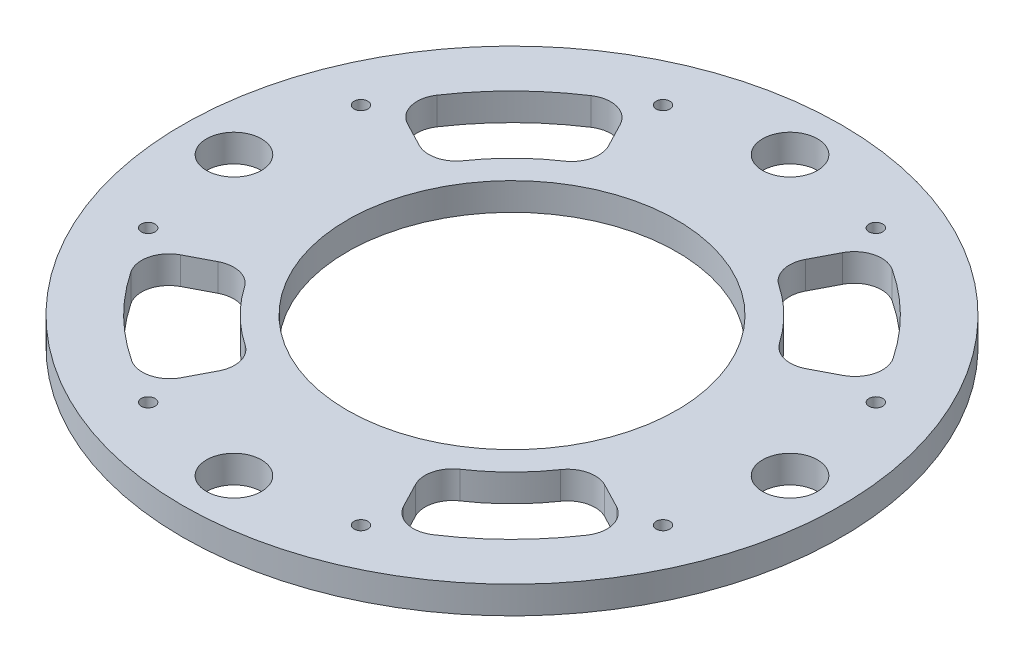
SolidWorks part; units mm, degrees
material "Acrylic (Medium-high impact)"
ref_plane "Front Plane" through (0, 0, 0) normal (0, 0, 1) x (1, 0, 0)
ref_plane "Top Plane" through (0, 0, 0) normal (0, 1, 0) x (1, 0, 0)
ref_plane "Right Plane" through (0, 0, 0) normal (1, 0, 0) x (0, 0, -1)
sketch "Sketch1" plane through (0, 0, 0) normal (0, 1, 0) x (1, 0, 0)
  circle A0 centre (0, 0) radius 76.2
  dimension "D1" = 152.4
extrude "Boss-Extrude1" add sketch "Sketch1" along normal blind 6.35
sketch "Sketch2" plane through (0, 6.35, 0) normal (0, 1, 0) x (1, 0, 0)
  circle A0 centre (0, 0) radius 35
  dimension "D1" = 70
extrude "Cut-Extrude1" cut sketch "Sketch2" against normal blind 6.35
sketch "Sketch3" plane through (0, 6.35, 0) normal (0, 1, 0) x (1, 0, 0)
  line L0 (-76.2, 0) -> (76.2, 0) construction
  line L1 (-51.5875, 51.5875) -> (51.5875, 51.5875) construction
  line L2 (-51.5875, 51.5875) -> (-51.5875, -51.5875) construction
  line L3 (-51.5875, -51.5875) -> (51.5875, -51.5875) construction
  line L4 (51.5875, 51.5875) -> (51.5875, -51.5875) construction
  circle A0 centre (0, 0) radius 76.2 construction
  circle A1 centre (-64.2875, 0) radius 6.35
  circle A2 centre (64.2875, 0) radius 6.35
  dimension "D1" = 12.7
  dimension "D2" = 12.7
  dimension "D3" = 12.7
  dimension "D4" = 12.7
extrude "Cut-Extrude2" cut sketch "Sketch3" against normal blind 10
sketch "Sketch4" plane through (0, 6.35, 0) normal (0, 1, 0) x (1, 0, 0)
  line L1 (50, -50) -> (-50, -50) construction
  line L2 (50, -50) -> (50, 50) construction
  line L3 (50, 50) -> (-50, 50) construction
  line L4 (-50, -50) -> (-50, 50) construction
  line L5 (50, -50) -> (-50, 50) construction
  line L6 (50, 50) -> (-50, -50) construction
  point P0 (0, 0)
  dimension "D1" = 100
  dimension "D2" = 100
sketch "Sketch5" plane through (0, 6.35, 0) normal (0, 1, 0) x (1, 0, 0)
  line L0 (-50, 24.6) -> (-59.525, 24.6) construction
  line L1 (-50, -50) -> (-50, 50) construction
  line L2 (-50, -24.6) -> (-59.525, -24.6) construction
  line L3 (50, 50) -> (-50, 50) construction
  line L4 (50, -50) -> (-50, -50) construction
  line L5 (-50, 50) -> (50, -50) construction
  line L6 (-50, -50) -> (50, 50) construction
  line L7 (24.6, 50) -> (24.6, 59.525) construction
  line L8 (-50, 50) -> (50, 50) construction
  line L9 (-50, 50) -> (-50, -50) construction
  line L10 (-50, -50) -> (50, -50) construction
  line L11 (50, 50) -> (50, -50) construction
  line L12 (-24.6, 50) -> (-24.6, 59.525) construction
  line L13 (50, 24.6) -> (59.525, 24.6) construction
  line L14 (-24.6, -50) -> (-24.6, -59.525) construction
  line L15 (24.6, -50) -> (24.6, -59.525) construction
  line L16 (50, -24.6) -> (59.525, -24.6) construction
  dimension "D1" = 25.4
  dimension "D2" = 25.4
  dimension "D3" = 9.525
  dimension "D4" = 9.525
sketch "Sketch7" plane through (0, 6.35, 0) normal (0, 1, 0) x (1, 0, 0)
  line L0 (0, 0) -> (0, 76.2) construction
  line L1 (0, 0) -> (53.8815, 53.8815) construction
  line L2 (0, 59.5249) -> (-24.5999, 59.5249) construction
  line L3 (0, 0) -> (76.2, 0) construction
  line L4 (0, -59.5249) -> (-24.5999, -59.5249) construction
  circle A0 centre (0, 0) radius 76.2 construction
  circle A1 centre (-24.5999, 59.5249) radius 1.5875
  circle A2 centre (24.5999, 59.5249) radius 1.5875
  circle A3 centre (24.5999, -59.5249) radius 1.5875
  circle A4 centre (-24.5999, -59.5249) radius 1.5875
  circle A5 centre (-59.5249, 24.5999) radius 1.5875
  circle A6 centre (-59.5249, -24.5999) radius 1.5875
  circle A7 centre (59.5249, 24.5999) radius 1.5875
  circle A8 centre (59.5249, -24.5999) radius 1.5875
  dimension "D1" = 45
  dimension "D2" = 59.5249
  dimension "D3" = 24.5999
extrude "Cut-Extrude4" cut sketch "Sketch7" against normal blind 10
sketch "Sketch8" plane through (0, 6.35, 0) normal (0, 1, 0) x (1, 0, 0)
  line L0 (0, 76.2) -> (0, -76.2) construction
  line L1 (0, 0) -> (53.8815, 53.8815) construction
  circle A0 centre (0, 0) radius 76.2 construction
  circle A1 centre (-64.2875, 0) radius 6.35
  circle A2 centre (64.2875, 0) radius 6.35
  circle A3 centre (0, -64.2875) radius 6.35
  circle A4 centre (0, 64.2875) radius 6.35
extrude "Cut-Extrude5" cut sketch "Sketch8" against normal blind 10
sketch "Sketch9" plane through (0, 6.35, 0) normal (0, 1, 0) x (1, 0, 0)
  circle A0 centre (0, 0) radius 38.1
  dimension "D1" = 76.2
extrude "Cut-Extrude6" cut sketch "Sketch9" against normal blind 10
sketch "Sketch10" plane through (0, 6.35, 0) normal (0, 1, 0) x (1, 0, 0)
  line L0 (0, 0) -> (-76.2, 0) construction
  line L1 (0, 0) -> (0, 76.2) construction
  line L2 (0, 0) -> (-53.8815, 53.8815) construction
  line L3 (-22.7447, 45.0673) -> (-25.6934, 50.7318)
  line L4 (-44.7067, 23.2729) -> (-50.3788, 26.2255)
  line L5 (44.7067, 23.2729) -> (50.3788, 26.2255)
  line L6 (22.7447, 45.0673) -> (25.6934, 50.7318)
  line L7 (22.7447, -45.0673) -> (25.6934, -50.7318)
  line L8 (44.7067, -23.2729) -> (50.3788, -26.2255)
  line L9 (-44.7067, -23.2729) -> (-50.3788, -26.2255)
  line L10 (-22.7447, -45.0673) -> (-25.6934, -50.7318)
  circle A0 centre (0, 0) radius 76.2 construction
  arc A1 (-24.83, 36.8683) -> (-36.5528, 25.2922) centre (0, 0) ccw
  arc A2 (-34.8066, 53.1108) -> (-52.7185, 35.3978) centre (0, 0) ccw
  circle A3 centre (0, 0) radius 38.1 construction
  arc A4 (-52.7185, 35.3978) -> (-50.3788, 26.2255) centre (-47.4467, 31.8581) ccw
  arc A5 (-44.7067, 23.2729) -> (-36.5528, 25.2922) centre (-41.7746, 28.9054) ccw
  arc A6 (-24.83, 36.8683) -> (-22.7447, 45.0673) centre (-28.3772, 42.1352) ccw
  arc A7 (-25.6934, 50.7318) -> (-34.8066, 53.1108) centre (-31.3259, 47.7997) ccw
  arc A8 (25.6934, 50.7318) -> (34.8066, 53.1108) centre (31.3259, 47.7997) cw
  arc A9 (24.83, 36.8683) -> (22.7447, 45.0673) centre (28.3772, 42.1352) cw
  arc A10 (44.7067, 23.2729) -> (36.5528, 25.2922) centre (41.7746, 28.9054) cw
  arc A11 (52.7185, 35.3978) -> (50.3788, 26.2255) centre (47.4467, 31.8581) cw
  arc A12 (34.8066, 53.1108) -> (52.7185, 35.3978) centre (0, 0) cw
  arc A13 (24.83, 36.8683) -> (36.5528, 25.2922) centre (0, 0) cw
  arc A14 (24.83, -36.8683) -> (36.5528, -25.2922) centre (0, 0) ccw
  arc A15 (34.8066, -53.1108) -> (52.7185, -35.3978) centre (0, 0) ccw
  arc A16 (52.7185, -35.3978) -> (50.3788, -26.2255) centre (47.4467, -31.8581) ccw
  arc A17 (44.7067, -23.2729) -> (36.5528, -25.2922) centre (41.7746, -28.9054) ccw
  arc A18 (24.83, -36.8683) -> (22.7447, -45.0673) centre (28.3772, -42.1352) ccw
  arc A19 (25.6934, -50.7318) -> (34.8066, -53.1108) centre (31.3259, -47.7997) ccw
  arc A20 (-25.6934, -50.7318) -> (-34.8066, -53.1108) centre (-31.3259, -47.7997) cw
  arc A21 (-24.83, -36.8683) -> (-22.7447, -45.0673) centre (-28.3772, -42.1352) cw
  arc A22 (-44.7067, -23.2729) -> (-36.5528, -25.2922) centre (-41.7746, -28.9054) cw
  arc A23 (-52.7185, -35.3978) -> (-50.3788, -26.2255) centre (-47.4467, -31.8581) cw
  arc A24 (-34.8066, -53.1108) -> (-52.7185, -35.3978) centre (0, 0) cw
  arc A25 (-24.83, -36.8683) -> (-36.5528, -25.2922) centre (0, 0) cw
  circle A26 centre (0, 0) radius 76.2
  dimension "D4" = 6.35
  dimension "D5" = 152.4
  dimension "D6" = 6.35
  dimension "D7" = 12.7
  dimension "D1" = 45
  dimension "D2" = 27.5
  dimension "D3" = 27.5
extrude "Cut-Extrude10" cut sketch "Sketch10" against normal blind 10 contours L3 A7 A2 A4 L4 A5 A1 A6 | A9 A13 A10 L5 A11 A12 A8 L6 | L7 A19 A15 A16 L8 A17 A14 A18 | A21 A25 A22 L9 A23 A24 A20 L10
